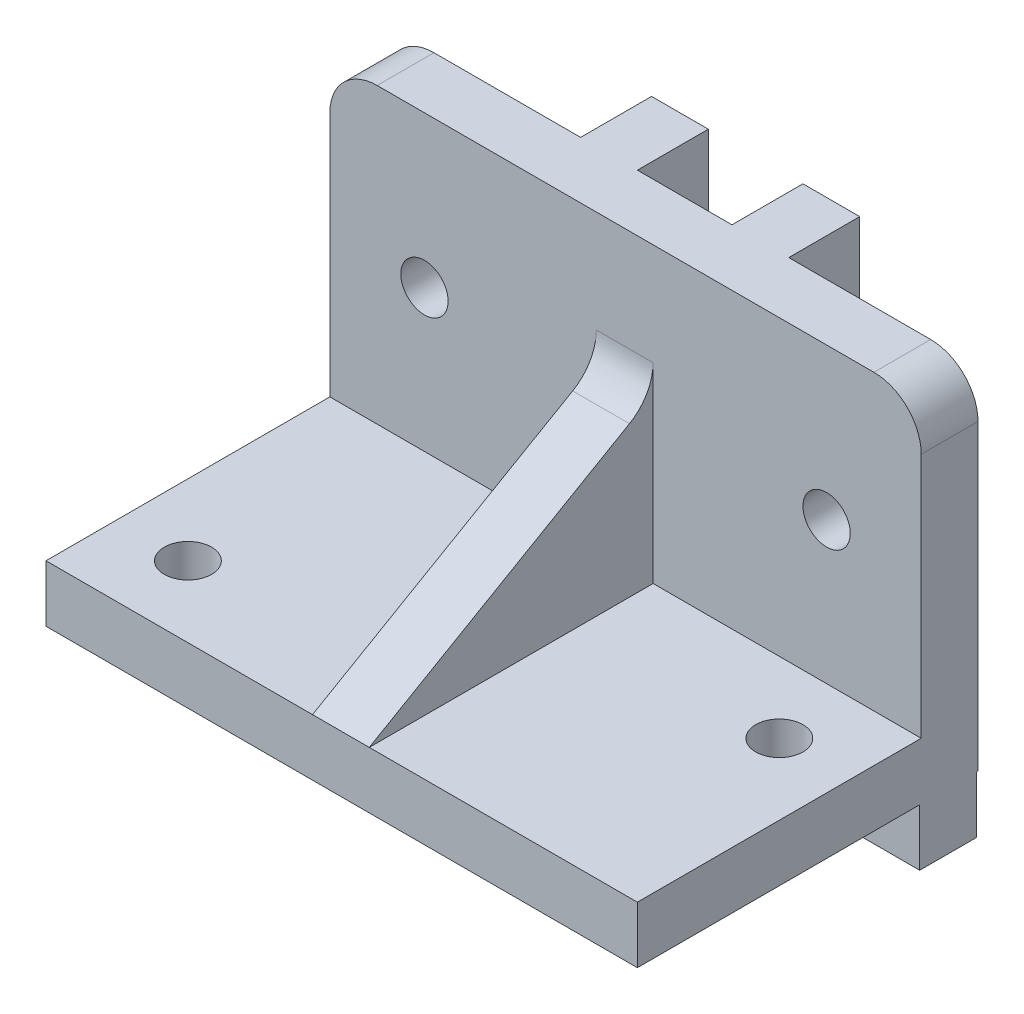
SolidWorks part; units mm, degrees
ref_plane "Front Plane" through (0, 0, 0) normal (0, 0, 1) x (1, 0, 0)
ref_plane "Top Plane" through (0, 0, 0) normal (0, 1, 0) x (1, 0, 0)
ref_plane "Right Plane" through (0, 0, 0) normal (1, 0, 0) x (0, 0, -1)
sketch "Sketch1" plane through (0, 0, 0) normal (0, 0, 1) x (1, 0, 0)
  line L1 (-62.5, 6) -> (62.5, 6)
  line L2 (-62.5, 6) -> (-62.5, -6)
  line L3 (-62.5, -6) -> (62.5, -6)
  line L4 (62.5, 6) -> (62.5, -6)
  line L5 (-62.5, 6) -> (62.5, -6) construction
  line L6 (-62.5, -6) -> (62.5, 6) construction
  point P0 (0, 0)
  dimension "D1" = 125
  dimension "D2" = 12
extrude "Boss-Extrude1" add sketch "Sketch1" against normal blind 72
sketch "Sketch2" plane through (0, 6, 0) normal (0, 1, 0) x (1, 0, 0)
  line L0 (62.5, 72) -> (62.5, 0) construction
  line L1 (-62.5, 72) -> (62.5, 72)
  line L2 (-62.5, 72) -> (-62.5, 60)
  line L3 (-62.5, 60) -> (62.5, 60)
  line L4 (62.5, 72) -> (62.5, 60)
  dimension "D1" = 12
extrude "Boss-Extrude2" add sketch "Sketch2" along normal blind 62
sketch "Sketch3" plane through (0, 0, -72) normal (0, 0, -1) x (-1, 0, 0)
  line L0 (-62.5, 68) -> (62.5, 68) construction
  line L1 (-22.5, 68) -> (-10.5, 68)
  line L2 (-22.5, 68) -> (-22.5, -6)
  line L3 (-22.5, -6) -> (-10.5, -6)
  line L4 (-10.5, 68) -> (-10.5, -6)
  line L5 (62.5, -6) -> (-62.5, -6) construction
  line L6 (-62.5, -6) -> (-62.5, 68) construction
  line L7 (9.5, 68) -> (21.5, 68)
  line L8 (9.5, 68) -> (9.5, -6)
  line L9 (9.5, -6) -> (21.5, -6)
  line L10 (21.5, 68) -> (21.5, -6)
  line L11 (62.5, 68) -> (62.5, -6) construction
  dimension "D1" = 12
  dimension "D2" = 12
  dimension "D3" = 20
  dimension "D4" = 40
  dimension "D5" = 41
extrude "Boss-Extrude3" add sketch "Sketch3" along normal blind 15
sketch "Sketch4" plane through (0, -6, 0) normal (0, -1, 0) x (1, 0, 0)
  line L0 (62.5, -72) -> (62.5, 0) construction
  line L1 (-62.5, -59.6752) -> (62.5, -59.6752)
  line L2 (-62.5, -59.6752) -> (-62.5, -71.6752)
  line L3 (-62.5, -71.6752) -> (62.5, -71.6752)
  line L4 (62.5, -59.6752) -> (62.5, -71.6752)
  line L5 (-62.5, -72) -> (-62.5, 0) construction
  point P7 (-62.5, 0)
  point P8 (62.5, -12)
  point P9 (-62.5, -59.6752)
  dimension "D1" = 12
extrude "Boss-Extrude4" add sketch "Sketch4" along normal blind 12
fillet "Fillet1" radius 10 2 edges at (62.5, 68, -66) (-62.5, 68, -66)
sketch "Sketch5" plane through (0, 0, -60) normal (0, 0, 1) x (1, 0, 0)
  line L0 (-52.5, 68) -> (52.5, 68) construction
  line L5 (-6.1698, 68) -> (5.8302, 68)
  line L6 (-6.1698, 68) -> (-6.1698, 6)
  line L7 (-6.1698, 6) -> (5.8302, 6)
  line L8 (5.8302, 68) -> (5.8302, 6)
  line L9 (-62.5, 6) -> (62.5, 6) construction
  dimension "D1" = 12
extrude "Boss-Extrude5" add sketch "Sketch5" along normal blind 60
sketch "Sketch6" plane through (-6.1698, 0, 0) normal (-1, 0, 0) x (0, 0, 1)
  line L0 (0, 6) -> (-60, 40.641)
  line L9 (-60, 68) -> (-60, 6) construction
  line L10 (0, 6) -> (-60, 6) construction
  line L11 (-60, 68) -> (-60, 40.641)
  line L12 (-60, 68) -> (0, 68)
  line L13 (0, 68) -> (0, 6)
  dimension "D1" = 30
extrude "Cut-Extrude4" cut sketch "Sketch6" against normal blind 12
fillet "Fillet2" radius 10 1 edges at (-0.1698, 40.641, -60)
hole_wizard "Ø10.0mm Dowel Slot1" positions "Sketch7" profile "Sketch8" size "Ø10.0" standard "DIN" slot yes end condition through all
sketch "Sketch7" plane through (0, 0, -60) normal (0, 0, 1) x (1, 0, 0)
  line L0 (-62.5, 6) -> (-6.1698, 6) construction
  line L1 (-62.5, 58) -> (-62.5, 6) construction
  line L2 (62.5, 58) -> (62.5, 6) construction
  line L3 (5.8302, 6) -> (62.5, 6) construction
  point P0 (42.5, 36)
  point P2 (-42.5, 36)
  dimension "D1" = 30
  dimension "D2" = 20
  dimension "D3" = 20
  dimension "D4" = 30
sketch "Sketch8" plane through (42.5, 36, -60) normal (1, 0, 0) x (0, -1, 0)
  line L0 (0, 0) -> (0, 27)
  line L1 (0, 27) -> (5, 27)
  line L2 (5, 27) -> (5, 0)
  line L5 (5, 0) -> (0, 0)
  line L11 (0, -6.35) -> (0, 107.95) construction
  dimension "Thru Hole Dia." = 10
  dimension "Thru Hole Depth" = 27
hole_wizard "Ø10.0mm Dowel Slot2" positions "Sketch9" profile "Sketch10" size "Ø10.0" standard "DIN" slot yes end condition through all
sketch "Sketch9" plane through (0, 6, 0) normal (0, 1, 0) x (1, 0, 0)
  line L0 (-62.5, 60) -> (-62.5, 0) construction
  line L1 (-6.1698, 0) -> (-62.5, 0) construction
  line L4 (62.5, 60) -> (62.5, 0) construction
  line L5 (5.8302, 60) -> (62.5, 60) construction
  point P0 (-47.5, 15)
  point P2 (47.5, 45)
  point P7 (-44.7705, 20.7773)
  point P18 (62.5, 44.5167)
  point P21 (0, 0)
  dimension "D1" = 15
  dimension "D2" = 15
  dimension "D3" = 15
  dimension "D4" = 15
sketch "Sketch10" plane through (-47.5, 6, -15) normal (1, 0, 0) x (0, 0, 1)
  line L0 (0, 0) -> (0, 24)
  line L1 (0, 24) -> (5, 24)
  line L2 (5, 24) -> (5, 0)
  line L5 (5, 0) -> (0, 0)
  line L11 (0, -6.35) -> (0, 107.95) construction
  dimension "Thru Hole Dia." = 10
  dimension "Thru Hole Depth" = 24
